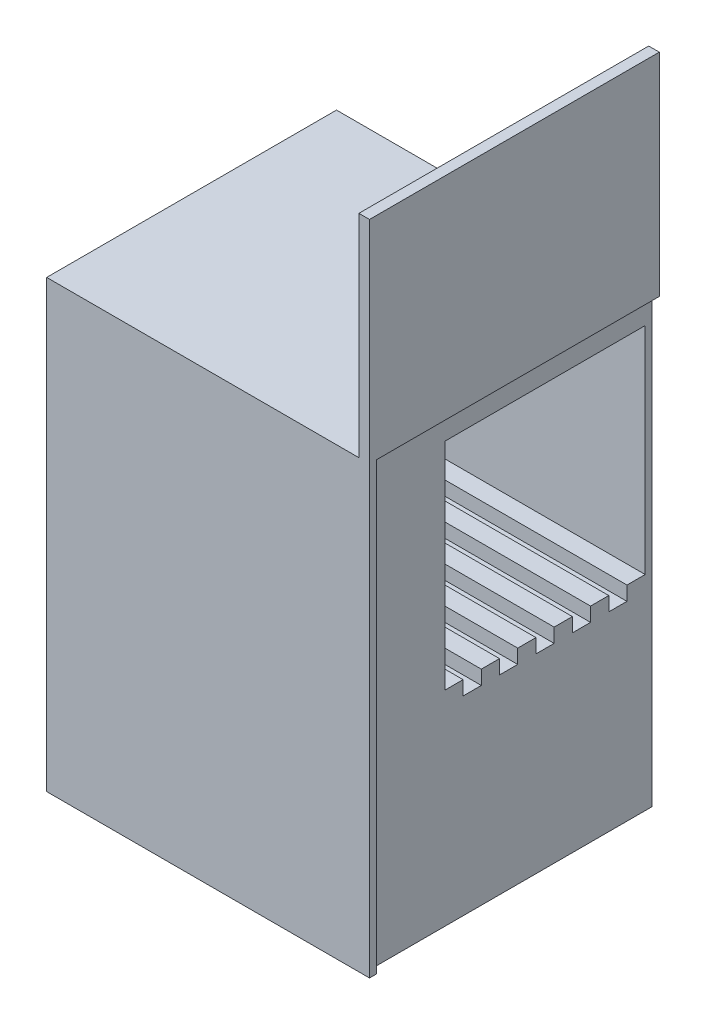
SolidWorks part; units mm, degrees
ref_plane "Спереди" through (0, 0, 0) normal (0, 0, 1) x (1, 0, 0)
ref_plane "Сверху" through (0, 0, 0) normal (0, 1, 0) x (1, 0, 0)
ref_plane "Справа" through (0, 0, 0) normal (1, 0, 0) x (0, 0, -1)
sketch "Эскиз1" plane through (0, 0, 0) normal (0, 0, 1) x (1, 0, 0)
  line L0 (624.7476, -71.1028) -> (350.7476, -71.1028) construction
  line L1 (350.7476, -71.1028) -> (618.7476, -71.1028)
  line L2 (350.7476, -71.1028) -> (350.7476, 306.8972)
  line L3 (350.7476, 306.8972) -> (618.7476, 306.8972)
  line L4 (618.7476, -71.1028) -> (618.7476, 306.8972)
  line L5 (350.7476, 526.4972) -> (350.7476, -71.1028) construction
  line L6 (618.7476, 526.4972) -> (618.7476, -71.1028) construction
  dimension "D1" = 378
extrude "Бобышка-Вытянуть1" add sketch "Эскиз1" along normal blind 246
sketch "Эскиз2" plane through (618.7476, 0, 0) normal (1, 0, 0) x (0, 0, -1)
  line L0 (6, 102.4972) -> (21.4545, 102.4972) construction
  line L1 (-6, 102.4972) -> (-176, 102.4972)
  line L2 (-6, 102.4972) -> (-6, 285.4972)
  line L3 (-6, 285.4972) -> (-176, 285.4972)
  line L4 (-176, 102.4972) -> (-176, 285.4972)
  line L7 (0, 306.8972) -> (0, -71.1028) construction
  dimension "D2" = 183
  dimension "D3" = 170
  dimension "D4" = 6
extrude "Вырез-Вытянуть1" cut sketch "Эскиз2" against normal blind 256
sketch "Эскиз7" plane through (618.7476, 0, 0) normal (1, 0, 0) x (0, 0, -1)
  line L0 (-240, -71.1028) -> (-246, -71.1028)
  line L1 (-240, 486.4972) -> (-240, 59.4972) construction
  line L2 (-246, -71.1028) -> (-246, 486.4972)
  line L3 (-246, 486.4972) -> (0, 486.4972)
  line L4 (0, 486.4972) -> (0, 306.8972)
  line L5 (0, 306.8972) -> (-240, 306.8972)
  line L6 (-246, 306.8972) -> (0, 306.8972) construction
  line L7 (-240, 306.8972) -> (-240, -71.1028)
  line L8 (-240, 486.4972) -> (0, 486.4972) construction
extrude "Бобышка-Вытянуть4" add sketch "Эскиз7" along normal up to surface (6 mm away) and the other way blind 3
sketch "Эскиз8" plane through (618.7476, 0, 0) normal (1, 0, 0) x (0, 0, -1)
  line L1 (-160.5455, 102.4972) -> (-145.0909, 102.4972)
  line L2 (-160.5455, 102.4972) -> (-160.5455, 90.4972)
  line L3 (-160.5455, 90.4972) -> (-145.0909, 90.4972)
  line L4 (-145.0909, 102.4972) -> (-145.0909, 90.4972)
  line L6 (21.4545, 102.4972) -> (21.4545, 90.4972) construction
  line L7 (-176, 102.4972) -> (-6, 102.4972) construction
  line L8 (-176, 285.4972) -> (-176, 102.4972) construction
  dimension "D1" = 15.4545
  dimension "D2" = 15.4545
extrude "Вырез-Вытянуть2" cut sketch "Эскиз8" against normal offset from surface (262 mm away) 6 up to face at (350.7476, 117.8972, 123)
pattern_linear "Линейный массив1" count 5 spacing 30.9091 along (0, 0, -1) of "Вырез-Вытянуть2"
equation "\"Ширина груза\"= 160"
equation "\"Глубина груза\"= 240"
equation "\"Высота груза\"= 160"
equation "\"Ширина ячейки\"= \"Ширина груза\" + 10"
equation "\"Глубина ячейки\"= \"Глубина груза\" + 10"
equation "\"Высота ячейки\"= \"Высота груза\" + 10 + 13"
equation "\"Колво ячеек ширина\"= 2"
equation "\"Колво ячеек высота\"= 2"
equation "\"Толщина стенки\" = \"Толщина тонких панелей\""
equation "\"Крепление дверцы\"= 5 "
equation "\"Ширина рейки\"= \"Толщина шестерни\""
equation "\"Высота рейки\"= 20"
equation "\"Высота пола\" = 2*\"Толщина тонких панелей\""
equation "\"Колво полозьев\"= 5"
equation "\"Отступ рейки\"= 20"
equation "\"Глубина каретки\"= \"Глубина ячейки\" + 30 + \"Мотор Y высота корпуса\" + 20"
equation "\"Длинна рейки\" = (\"Ширина ячейки\"+\"Толщина вертикальных стенок\"+\"Крепление дверцы\")*\"Колво ячеек ширина\"+\"Ширина ячейки выгрузки\"*\"Колво выгрузки\"+\"Толщина вертикальных стенок\"+2*\"Отступ крепления мотора фиксации\"-\"Крепление дверцы\"*\"Колво ячеек ширина\""
equation "\"Отступ шпильки\"= 26"
equation "\"Диаметр шпильки\"= 5"
equation "\"Длинна шпильки\" = (\"Высота ячейки\"+\"Толщина горизонтальных плит\"+\"Высота пола\")*\"Колво ячеек высота\"+2*(\"Толщина горизонтальных плит\"+\"Отступ рейки\")"
equation "\"Ширина пластины\"= 50  "
equation "\"D2@Эскиз2\"=\"Высота ячейки\""
equation "\"D3@Эскиз2\"=\"Ширина ячейки\""
equation "\"Высота зона выгрузки\"= \"Высота ячейки\" * 2 + \"Толщина стенки\" * 2"
equation "\"D1@Бобышка-Вытянуть1\"=\"Ширина ячейки выгрузки\" + \"Толщина стенки\""
equation "\"Колво выгрузки\"= 1"
equation "\"D1@Вырез-Вытянуть1\"=\"Глубина ячейки\" + \"Толщина стенки\" "
equation "\"Ширина ячейки выгрузки\" = \"Ширина ячейки\"+\"Толщина вертикальных стенок\"+2*\"Отступ крепления мотора фиксации\""
equation "\"Отступ крепления мотора фиксации\" = (\"Ширина пластины\"+20-\"Толщина вертикальных стенок\")/2"
equation "\"D4@Эскиз2\"=\"Толщина стенки\""
equation "\"D1@Эскиз1\"=\"Высота зона выгрузки\""
equation "\"Мотор X ширина корпуса\"= 42.3"
equation "\"Мотор X высота корпуса\"= 42.3"
equation "\"Мотор X длина корпуса\"= 40"
equation "\"Мотор X вылет вала\"= 19.8"
equation "\"Мотор Y ширина корпуса\"= 42.3"
equation "\"Мотор Y высота корпуса\"= 42.3"
equation "\"Мотор Y длина корпуса\"= 48"
equation "\"Мотор Y вылет вала\"= 30"
equation "\"Мотор Z ширина корпуса\"= 42"
equation "\"Мотор Z высота корпуса\"= 42"
equation "\"Мотор Z длина корпуса\"= 40"
equation "\"Мотор Z вылет вала\"= 23"
equation "\"Мотор диаметр вала ПРЕДВ\"= 5"
equation "\"Мотор шаг крепления ПРЕДВ\"= 31"
equation "\"Мотор диаметр отверстий ПРЕДВ\"= 3"
equation "\"Мотор глубина отверстий ПРЕДВ\"= 4.5"
equation "\"Мотор диаметр буртика ПРЕДВ\"= 22"
equation "\"Мотор высота буртика ПРЕДВ\"= 2"
equation "\"Мотор диаметр шкива ПРЕДВ\"= 16"
equation "\"Мотор длина шкива ПРЕДВ\"= 12"
equation "\"Мотор отступ шкива ПРЕДВ\"= 5"
equation "\"Мотор X шаг градусов\"= 1.8"
equation "\"Мотор X ток А\"= 1.5"
equation "\"Мотор X сопротивление Ом\"= 1.3"
equation "\"Мотор X индуктивность мГн\"= 2"
equation "\"Мотор Y шаг градусов\"= 1.8"
equation "\"Мотор Y ток А\"= 2.2"
equation "\"Мотор Y сопротивление Ом\"= 0.9"
equation "\"Мотор Y индуктивность мГн\"= 2"
equation "\"Мотор Z шаг градусов\"= 1.8"
equation "\"Мотор Z ток А\"= 1"
equation "\"Мотор Z сопротивление Ом\"= 4"
equation "\"Мотор Z индуктивность мГн\"= 8"
equation "\"Мотор Y диаметр ротора\"= 25.78"
equation "\"D1@Эскиз8\"=\"Ширина ячейки\"/(\"Колво полозьев\"*2+1)"
equation "\"D1@Вырез-Вытянуть2\"=\"Толщина стенки\""
equation "\"D3@Линейный массив1\"=\"Ширина ячейки\"/(\"Колво полозьев\"*2+1)*2"
equation "\"D1@Линейный массив1\"=\"Колво полозьев\""
equation "\"D2@Эскиз8\"=\"Ширина ячейки\"/(\"Колво полозьев\"*2+1)"
equation "\"Толщина тонких панелей\" = 6"
equation "\"Толщина вертикальных стенок\" = 6"
equation "\"Толщина горизонтальных плит\" = 6"
equation "\"Базовая высота корпуса\"= (\"Высота ячейки\"+\"Толщина тонких панелей\"+\"Высота пола\")*\"Колво ячеек высота\"+6*\"Толщина тонких панелей\"+\"Мотор X ширина корпуса\"+\"Мотор Y ширина корпуса\"+75"
equation "\"Высота корпуса\"= (\"Высота ячейки\"+\"Толщина горизонтальных плит\"+\"Высота пола\")*\"Колво ячеек высота\"+2*\"Толщина горизонтальных плит\"+4*\"Толщина тонких панелей\"+\"Мотор X ширина корпуса\"+\"Мотор Y ширина корпуса\"+75"
equation "\"Смещение центра корпуса\"= (\"Высота корпуса\"-\"Базовая высота корпуса\")/2-(\"Толщина горизонтальных плит\"-\"Толщина тонких панелей\")"
equation "\"Отметка пола\"= -\"Базовая высота корпуса\"/2+\"Толщина тонких панелей\""
equation "\"Отметка потолка\"= \"Отметка пола\"+\"Высота корпуса\"-2*\"Толщина горизонтальных плит\""
equation "\"Отметка верхней полки\"= \"Отметка потолка\"-(28+\"Толщина тонких панелей\")-\"Высота ячейки\"-\"Высота пола\""
equation "\"Отметка нижней полки\"= \"Отметка верхней полки\"-\"Высота ячейки\"-\"Высота пола\"-\"Толщина горизонтальных плит\""
equation "\"Толщина шестерни\"= 10"
